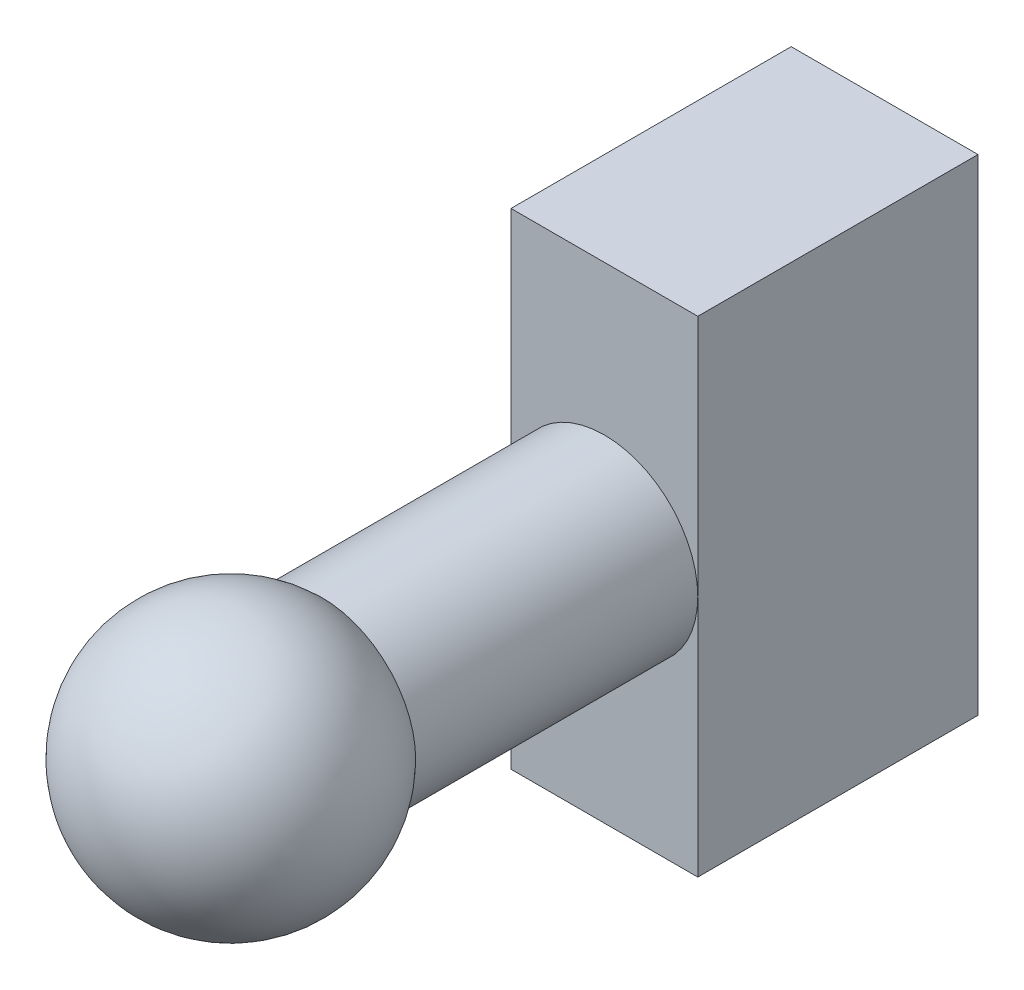
SolidWorks part; units mm, degrees
ref_plane "Front" through (0, 0, 0) normal (0, 0, 1) x (1, 0, 0)
ref_plane "Top" through (0, 0, 0) normal (0, 1, 0) x (1, 0, 0)
ref_plane "Right" through (0, 0, 0) normal (1, 0, 0) x (0, 0, -1)
sketch "Sketch1" plane through (0, 0, 0) normal (0, 0, 1) x (1, 0, 0)
  line L1 (5, -13) -> (-5, -13)
  line L2 (5, -13) -> (5, 13)
  line L3 (5, 13) -> (-5, 13)
  line L4 (-5, -13) -> (-5, 13)
  line L5 (5, -13) -> (-5, 13) construction
  line L6 (5, 13) -> (-5, -13) construction
  point P0 (0, 0)
  dimension "D1" = 26
  dimension "D2" = 10
extrude "Boss-Extrude1" add sketch "Sketch1" along normal blind 15
sketch "Sketch2" plane through (0, 0, 15) normal (0, 0, 1) x (1, 0, 0)
  circle A0 centre (0, 0) radius 5
extrude "Boss-Extrude2" add sketch "Sketch2" along normal blind 20
sketch "Sketch3" plane through (0, 0, 35) normal (0, 0, 1) x (1, 0, 0)
  line L0 (-7, 0) -> (7, 0)
  arc A0 (7, 0) -> (-7, 0) centre (0, 0) ccw
  dimension "D1" = 7
revolve "Revolve1" add sketch "Sketch3" angle 360 about L0
